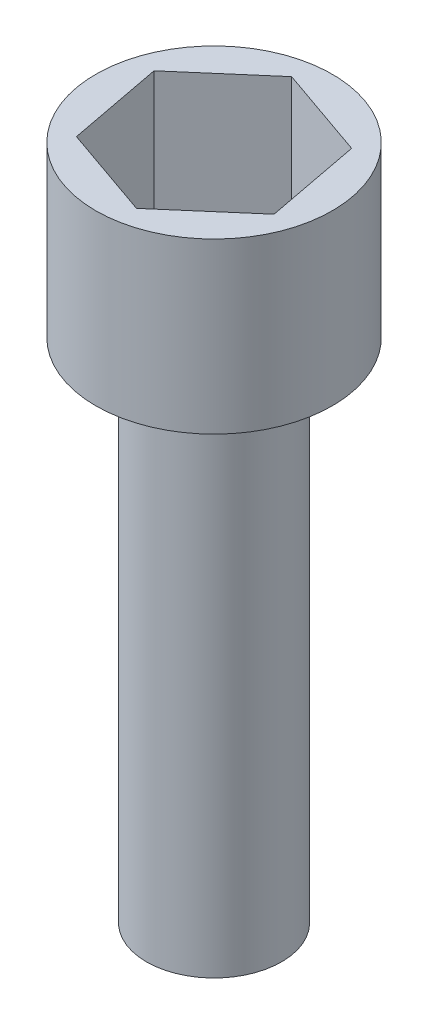
SolidWorks part; units mm, degrees
ref_plane "Plan de face" through (0, 0, 0) normal (0, 0, 1) x (1, 0, 0)
ref_plane "Plan de dessus" through (0, 0, 0) normal (0, 1, 0) x (1, 0, 0)
ref_plane "Plan de droite" through (0, 0, 0) normal (1, 0, 0) x (0, 0, -1)
sketch "Esquisse1" plane through (0, 0, 0) normal (0, 1, 0) x (1, 0, 0)
  circle A0 centre (0, 0) radius 2
extrude "Boss.-Extru.2" add sketch "Esquisse1" along normal blind 15
sketch "Esquisse4" plane through (0, 15, 0) normal (0, 1, 0) x (1, 0, 0)
  circle A0 centre (0, 0) radius 3.5
extrude "Boss.-Extru.5" add sketch "Esquisse4" along normal blind 5
sketch "Esquisse6" plane through (0, 20, 0) normal (0, 1, 0) x (1, 0, 0)
  line L1 (0.54, -2.8358) -> (2.7259, -0.9503)
  line L2 (2.7259, -0.9503) -> (2.1859, 1.8855)
  line L3 (2.1859, 1.8855) -> (-0.54, 2.8358)
  line L4 (-0.54, 2.8358) -> (-2.7259, 0.9503)
  line L5 (-2.7259, 0.9503) -> (-2.1859, -1.8855)
  line L6 (-2.1859, -1.8855) -> (0.54, -2.8358)
  circle A0 centre (0, 0) radius 2.5 construction
extrude "Enlèv. mat.-Extru.3" cut sketch "Esquisse6" against normal blind 4
